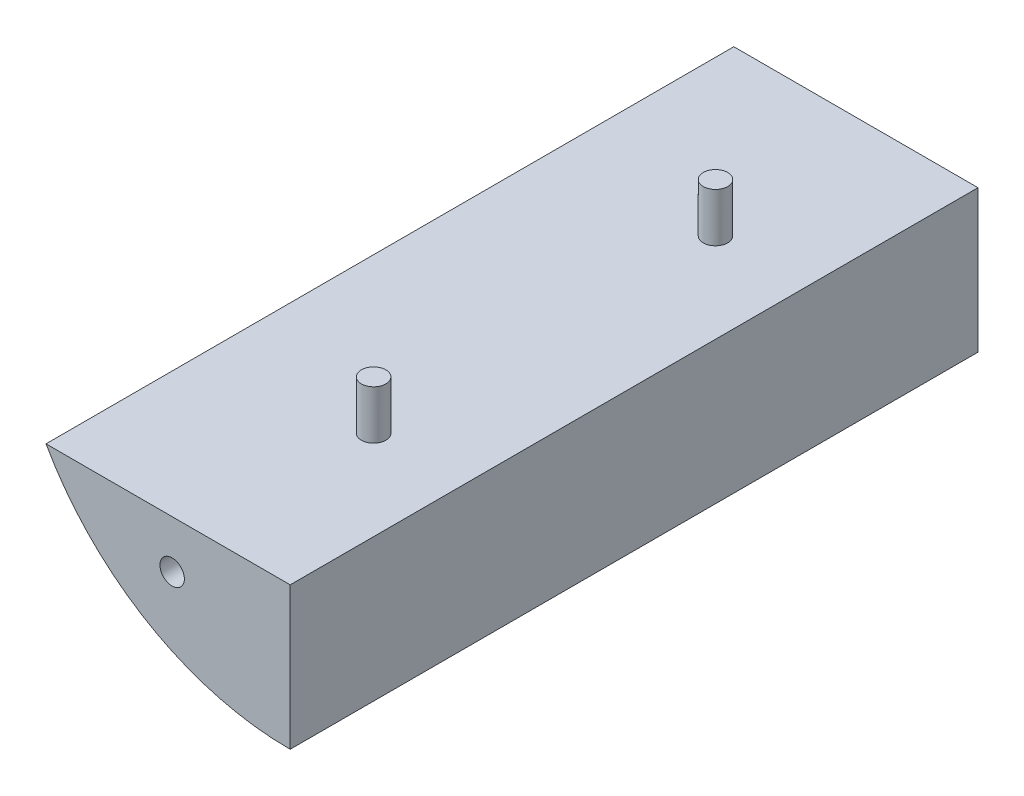
SolidWorks part; units mm, degrees
ref_plane "Plan de face" through (0, 0, 0) normal (0, 0, 1) x (1, 0, 0)
ref_plane "Plan de dessus" through (0, 0, 0) normal (0, 1, 0) x (1, 0, 0)
ref_plane "Plan de droite" through (0, 0, 0) normal (1, 0, 0) x (0, 0, -1)
sketch "Esquisse1" plane through (0, 0, 0) normal (0, 0, 1) x (1, 0, 0)
  line L0 (0, 0) -> (60, 0)
  line L1 (60, 0) -> (60, -35)
  arc A0 (0, 0) -> (60, -35) centre (59.7935, 33.5745) ccw
extrude "Boss.-Extru.1" add sketch "Esquisse1" along normal blind 169
sketch "Esquisse2" plane through (0, 0, 0) normal (0, 0, -1) x (-1, 0, 0)
  circle A0 centre (-31, -12) radius 3.3073
extrude "Enlèv. mat.-Extru.1" cut sketch "Esquisse2" against normal blind 22
sketch "Esquisse3" plane through (0, 0, 0) normal (0, 1, 0) x (1, 0, 0)
  circle A2 centre (38, -42.5) radius 3
extrude "Boss.-Extru.3" add sketch "Esquisse3" along normal blind 12
sketch "Esquisse4" plane through (0, 0, 0) normal (0, 1, 0) x (1, 0, 0)
  line L0 (0, -169) -> (0, 0) construction
  line L1 (60, -169) -> (0, -169) construction
  circle A0 centre (38, -126.5) radius 3
  dimension "D1" = 38
  dimension "D2" = 42.5
extrude "Boss.-Extru.4" add sketch "Esquisse4" along normal blind 12
sketch "Esquisse5" plane through (0, 0, 169) normal (0, 0, 1) x (1, 0, 0)
  circle A0 centre (31, -11.7703) radius 3
extrude "Enlèv. mat.-Extru.2" cut sketch "Esquisse5" against normal blind 22
